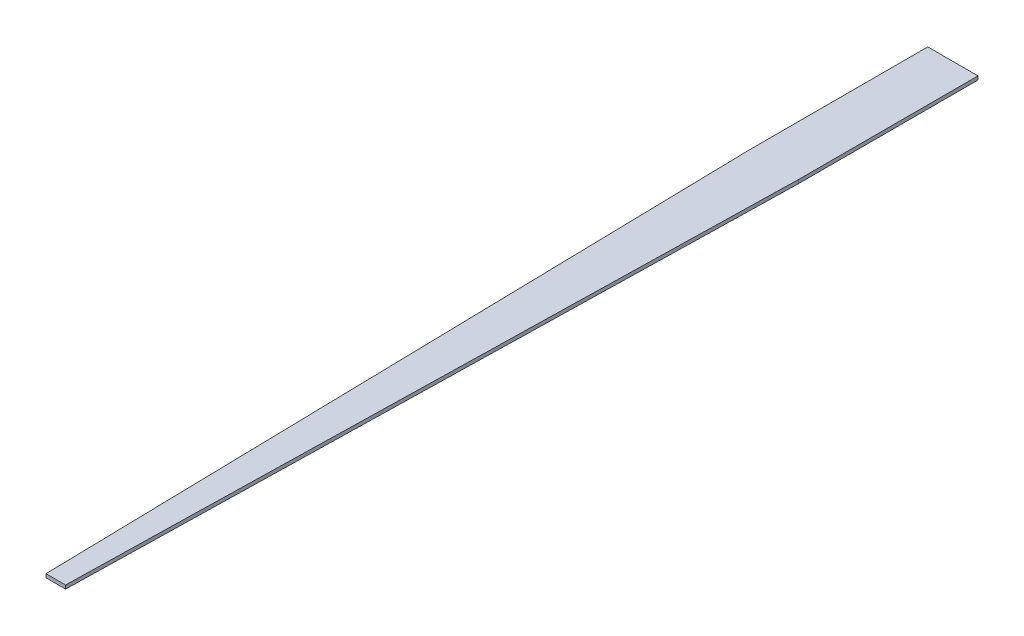
SolidWorks part; units mm, degrees
ref_plane "Front Plane" through (0, 0, 0) normal (0, 0, 1) x (1, 0, 0)
ref_plane "Top Plane" through (0, 0, 0) normal (0, 1, 0) x (1, 0, 0)
ref_plane "Right Plane" through (0, 0, 0) normal (1, 0, 0) x (0, 0, -1)
sketch "Sketch1" plane through (0, 0, 0) normal (0, 1, 0) x (1, 0, 0)
  line L0 (4.275, 200) -> (9.725, 200)
  line L1 (4.275, 0) -> (9.725, 0)
  line L8 (4.275, 0) -> (9.725, 0)
  line L11 (14, 200) -> (0, 200)
  line L13 (9.725, 0) -> (14, 200)
  line L14 (4.275, 0) -> (0, 200)
extrude "Boss-Extrude1" add sketch "Sketch1" along normal blind 1 contours L14 L1 L13 L11 L0
sketch "Sketch2" plane through (0, 0, 0) normal (0, -1, 0) x (1, 0, 0)
  line L0 (0, -200) -> (0, -250)
  line L1 (0, -250) -> (14, -250)
  line L2 (14, -250) -> (14, -200)
  line L3 (14, -200) -> (0, -200)
extrude "Boss-Extrude2" add sketch "Sketch2" against normal up to surface (1 mm away) up to face at (7, 1, -100)
sketch "Sketch3" plane through (0, 0, 0) normal (0, -1, 0) x (1, 0, 0)
  line L0 (7, -250) -> (7, 0) construction
  line L1 (0, -250) -> (14, -250) construction
  line L2 (4.275, 0) -> (9.725, 0) construction
ref_plane "Plane1" through (7, 0, 0) normal (1, 0, 0) x (0, 0, -1)
